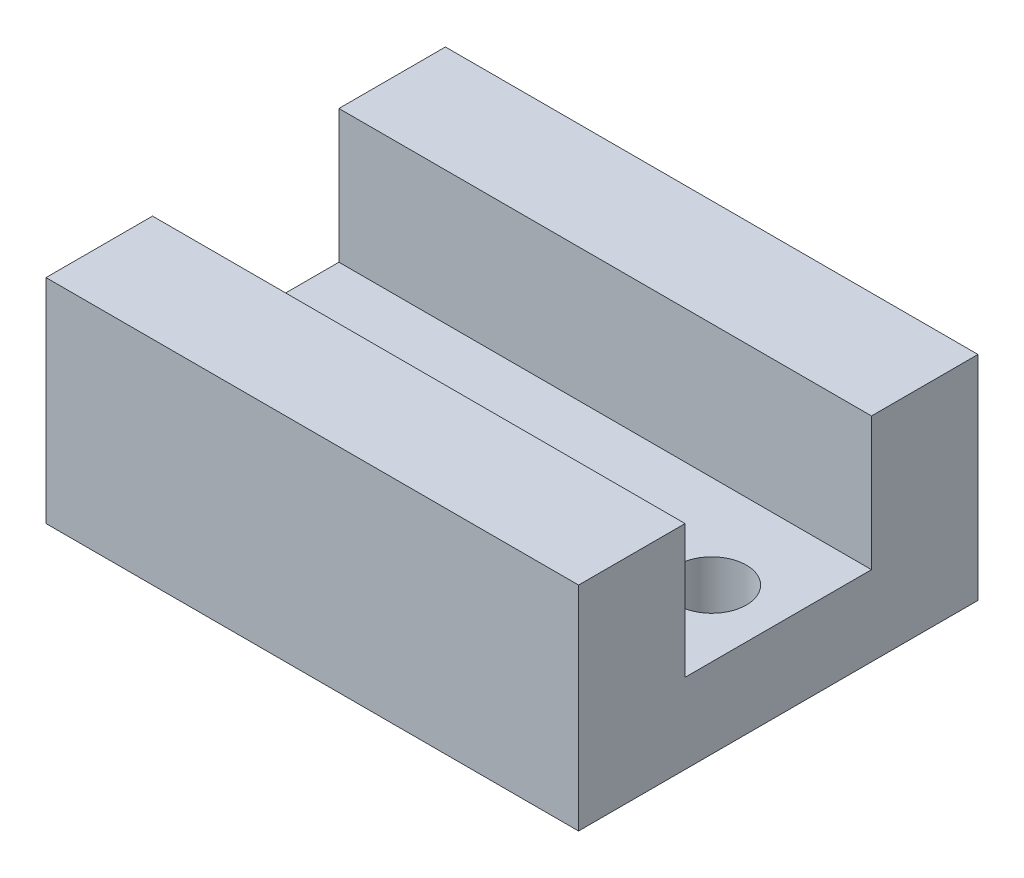
SolidWorks part; units mm, degrees
ref_plane "前视基准面" through (0, 0, 0) normal (0, 0, 1) x (1, 0, 0)
ref_plane "上视基准面" through (0, 0, 0) normal (0, 1, 0) x (1, 0, 0)
ref_plane "右视基准面" through (0, 0, 0) normal (1, 0, 0) x (0, 0, -1)
sketch "草图1" plane through (0, 0, 0) normal (0, 1, 0) x (1, 0, 0)
  line L0 (0, 0) -> (7.5, 0) construction
  line L1 (-10, 7.5) -> (10, 7.5)
  line L2 (-10, 7.5) -> (-10, -7.5)
  line L3 (-10, -7.5) -> (10, -7.5)
  line L4 (10, 7.5) -> (10, -7.5)
  line L5 (-10, 7.5) -> (10, -7.5) construction
  line L6 (-10, -7.5) -> (10, 7.5) construction
  line L7 (7.5, 0) -> (-7.5, 0) construction
  circle A0 centre (7.5, 0) radius 1.3
  circle A1 centre (-7.5, 0) radius 1.3
  point P0 (0, 0)
  dimension "D5" = 2.6
  dimension "D6" = 2.6
  dimension "D1" = 15
  dimension "D2" = 20
  dimension "D3" = 15
  dimension "D4" = 7.5
extrude "凸台-拉伸1" add sketch "草图1" along normal blind 3
ref_plane "基准面1" through (0, 3, 0) normal (0, 1, 0) x (1, 0, 0)
sketch "草图2" plane through (0, 3, 0) normal (0, 1, 0) x (1, 0, 0)
  line L0 (10, -7.5) -> (10, 7.5) construction
  line L1 (-10, 7.5) -> (10, 7.5)
  line L2 (-10, 7.5) -> (-10, 3.5)
  line L3 (-10, 3.5) -> (10, 3.5)
  line L4 (10, 7.5) -> (10, 3.5)
  line L6 (-10, -7.5) -> (10, -7.5)
  line L7 (-10, -7.5) -> (-10, -3.5)
  line L8 (-10, -3.5) -> (10, -3.5)
  line L9 (10, -7.5) -> (10, -3.5)
  dimension "D1" = 4
  dimension "D2" = 4
extrude "凸台-拉伸2" add sketch "草图2" along normal blind 5
